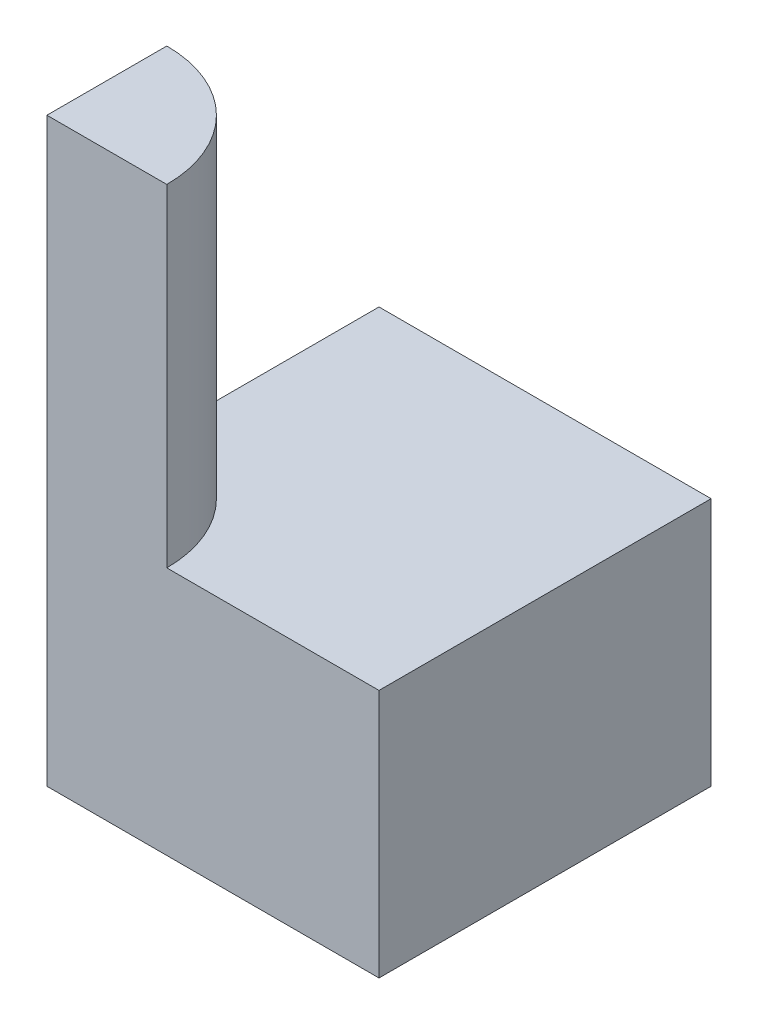
SolidWorks part; units mm, degrees
ref_plane "Front Plane" through (0, 0, 0) normal (0, 0, 1) x (1, 0, 0)
ref_plane "Top Plane" through (0, 0, 0) normal (0, 1, 0) x (1, 0, 0)
ref_plane "Right Plane" through (0, 0, 0) normal (1, 0, 0) x (0, 0, -1)
sketch "Sketch1" plane through (0, 0, 0) normal (0, 1, 0) x (1, 0, 0)
  line L1 (0, 0) -> (25.4, 0)
  line L2 (0, 0) -> (0, 25.4)
  line L3 (0, 25.4) -> (25.4, 25.4)
  line L4 (25.4, 0) -> (25.4, 25.4)
  dimension "D1" = 25.4
  dimension "D2" = 25.4
extrude "Boss-Extrude1" add sketch "Sketch1" along normal blind 19.05
sketch "Sketch3" plane through (0, 19.05, 0) normal (0, 1, 0) x (1, 0, 0)
  line L0 (0, 25.4) -> (0, 0) construction
  line L1 (0, 0) -> (25.4, 0) construction
  line L2 (0, 0) -> (0, 9.1694)
  line L3 (0, 0) -> (9.1694, 0)
  arc A0 (0, 9.1694) -> (9.1694, 0) centre (0, 0) cw
  dimension "D1" = 9.1694
extrude "Boss-Extrude2" add sketch "Sketch3" along normal blind 25.4
